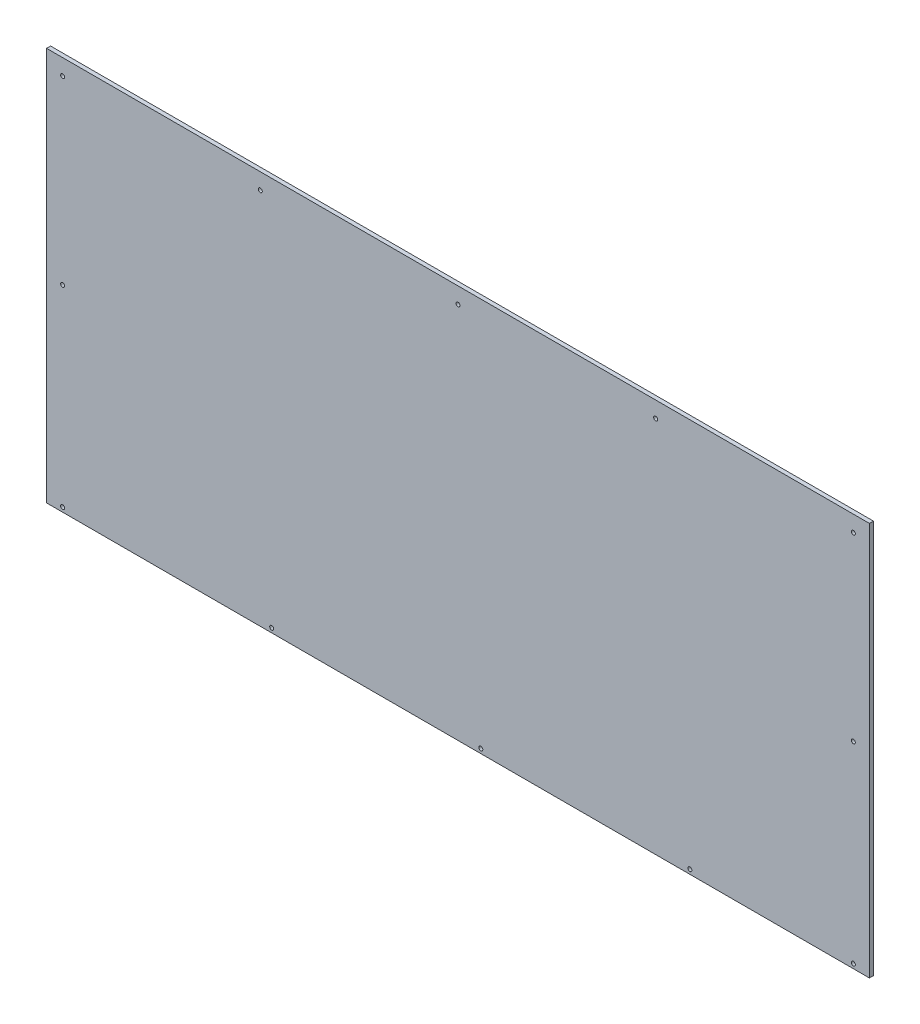
SolidWorks part; units mm, degrees
ref_plane "Alzado" through (0, 0, 0) normal (0, 0, 1) x (1, 0, 0)
ref_plane "Planta" through (0, 0, 0) normal (0, 1, 0) x (1, 0, 0)
ref_plane "Vista lateral" through (0, 0, 0) normal (1, 0, 0) x (0, 0, -1)
sketch "Croquis1" plane through (0, 0, 0) normal (0, 0, 1) x (1, 0, 0)
  line L1 (-650, 311) -> (650, 311)
  line L2 (-650, 311) -> (-650, -311)
  line L3 (-650, -311) -> (650, -311)
  line L4 (650, 311) -> (650, -311)
  line L5 (-650, 311) -> (650, -311) construction
  line L6 (-650, -311) -> (650, 311) construction
  point P0 (0, 0)
  dimension "D1" = 622
  dimension "D2" = 1300
extrude "Saliente-Extruir1" add sketch "Croquis1" along normal blind 6.35
sketch "Croquis2" plane through (0, 0, 6.35) normal (0, 0, 1) x (1, 0, 0)
  line L0 (650, 311) -> (-650, 311) construction
  line L1 (-624.6, -285.6) -> (624.6, -285.6) construction
  line L2 (-624.6, -285.6) -> (-624.6, 285.6) construction
  line L3 (-624.6, 285.6) -> (624.6, 285.6) construction
  line L4 (624.6, -285.6) -> (624.6, 285.6) construction
  line L5 (-624.6, -285.6) -> (624.6, 285.6) construction
  line L6 (-624.6, 285.6) -> (624.6, -285.6) construction
  line L7 (-650, 311) -> (-650, -311) construction
  line L8 (0, 0) -> (0, 285.6) construction
  line L9 (0, 0) -> (159.2342, 0) construction
  line L10 (-624.6, 285.6) -> (0, 285.6) construction
  line L11 (0, 285.6) -> (-312.3, 285.6) construction
  line L12 (0, 285.6) -> (624.6, 285.6) construction
  line L13 (624.6, 285.6) -> (312.3, 285.6) construction
  line L14 (-624.6, 0) -> (0, 0) construction
  line L15 (-624.6, -311) -> (-624.6, -304) construction
  line L16 (-650, -311) -> (650, -311) construction
  circle A0 centre (-624.6, 285.6) radius 3.175
  circle A1 centre (0, 285.6) radius 3.175
  circle A2 centre (624.6, 285.6) radius 3.175
  circle A3 centre (-312.3, 285.6) radius 3.175
  circle A4 centre (312.3, 285.6) radius 3.175
  circle A5 centre (-624.6, 0) radius 3.175
  circle A6 centre (624.6, 0) radius 3.175
  circle A7 centre (-624.6, -304) radius 3.175
  circle A8 centre (624.6, -304) radius 3.175
  circle A9 centre (-294.3, -304) radius 3.175
  circle A10 centre (36, -304) radius 3.175
  circle A11 centre (366.3, -304) radius 3.175
  point P0 (0, 0)
  dimension "D3" = 6.35
  dimension "D4" = 6.35
  dimension "D5" = 6.35
  dimension "D6" = 6.35
  dimension "D7" = 6.35
  dimension "D8" = 6.35
  dimension "D1" = 25.4
  dimension "D2" = 25.4
  dimension "D9" = 7
  dimension "D11" = 330.3
  dimension "D10" = 4
extrude "Cortar-Extruir2" cut sketch "Croquis2" against normal blind 6.35
